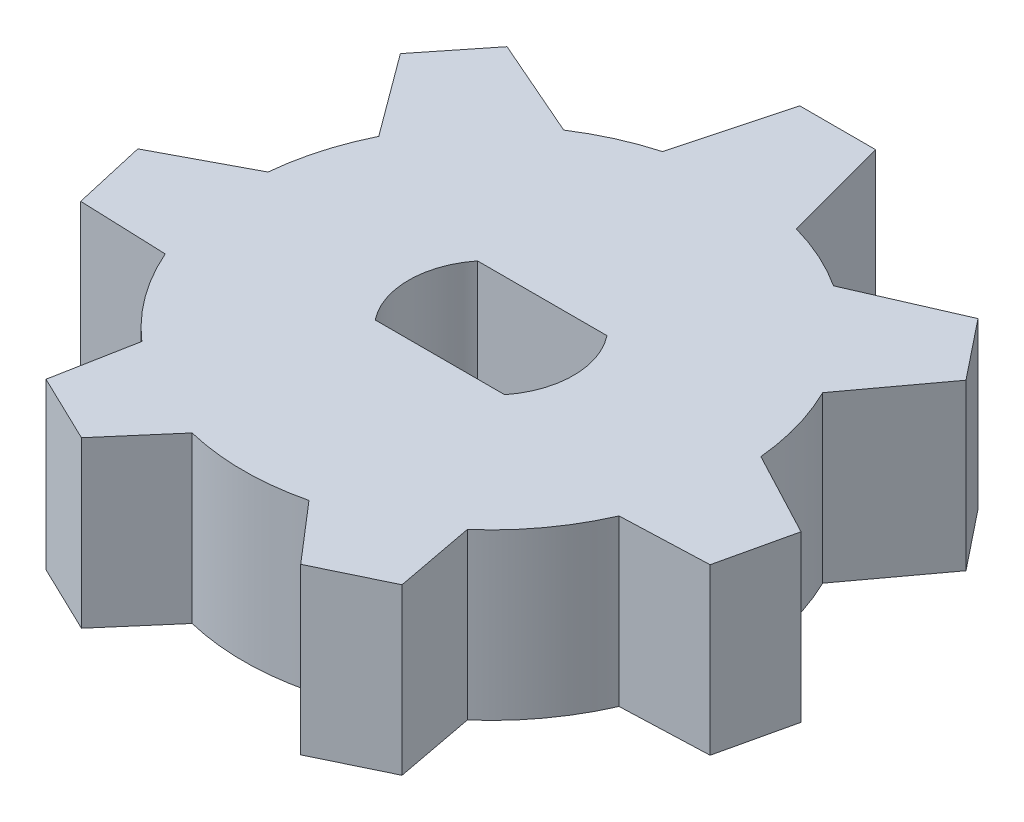
SolidWorks part; units mm, degrees
ref_plane "Ebene vorne" through (0, 0, 0) normal (0, 0, 1) x (1, 0, 0)
ref_plane "Ebene oben" through (0, 0, 0) normal (0, 1, 0) x (1, 0, 0)
ref_plane "Ebene rechts" through (0, 0, 0) normal (1, 0, 0) x (0, 0, -1)
sketch "Skizze1" plane through (0, 0, 0) normal (0, 1, 0) x (1, 0, 0)
  circle A0 centre (0, 0) radius 7.5
  dimension "D1" = 15
extrude "Aufsatz-Linear austragen1" add sketch "Skizze1" along normal blind 5
sketch "Skizze2" plane through (0, 5, 0) normal (0, 1, 0) x (1, 0, 0)
  line L0 (0, 0) -> (0, 9.7137) construction
  line L1 (-1.15, 10.5) -> (1.15, 10.5)
  line L2 (1.15, 10.5) -> (2.0878, 7)
  line L3 (2.0878, 7) -> (-2.0878, 7)
  line L4 (-2.0878, 7) -> (-1.15, 10.5)
  line L5 (-2.75, 0) -> (2.75, 0) construction
  point P6 (0, 0)
  dimension "D1" = 2.3
  dimension "D2" = 1.15
  dimension "D3" = 75
  dimension "D4" = 75
  dimension "D5" = 3.5
  dimension "D6" = 7
  dimension "D7" = 3.5
extrude "Aufsatz-Linear austragen2" add sketch "Skizze2" against normal blind 5
pattern_circular "Kreismuster1" count 7 over 360 about axis through (0, 0, -0.4573) along (0, 1, 0) of "Aufsatz-Linear austragen2"
sketch "Skizze3" plane through (0, 5, 0) normal (0, 1, 0) x (1, 0, 0)
  line L1 (-3.3018, 3.9417) -> (3.5077, 3.9417)
  line L2 (-3.3018, 3.9417) -> (-3.3018, 1.55)
  line L3 (-3.3018, 1.55) -> (3.5077, 1.55)
  line L4 (3.5077, 3.9417) -> (3.5077, 1.55)
  line L9 (-3.3018, -1.55) -> (3.5077, -1.55)
  line L10 (-3.3018, -1.55) -> (-3.3018, -3.7342)
  line L11 (-3.3018, -3.7342) -> (3.5077, -3.7342)
  line L12 (3.5077, -1.55) -> (3.5077, -3.7342)
  circle A0 centre (0, 0) radius 2.5
  dimension "D1" = 5
  dimension "D2" = 3.1
  dimension "D3" = 1.55
extrude "Schnitt-Linear austragen1" cut sketch "Skizze3" against normal blind 5 contours L9 A0 L3
